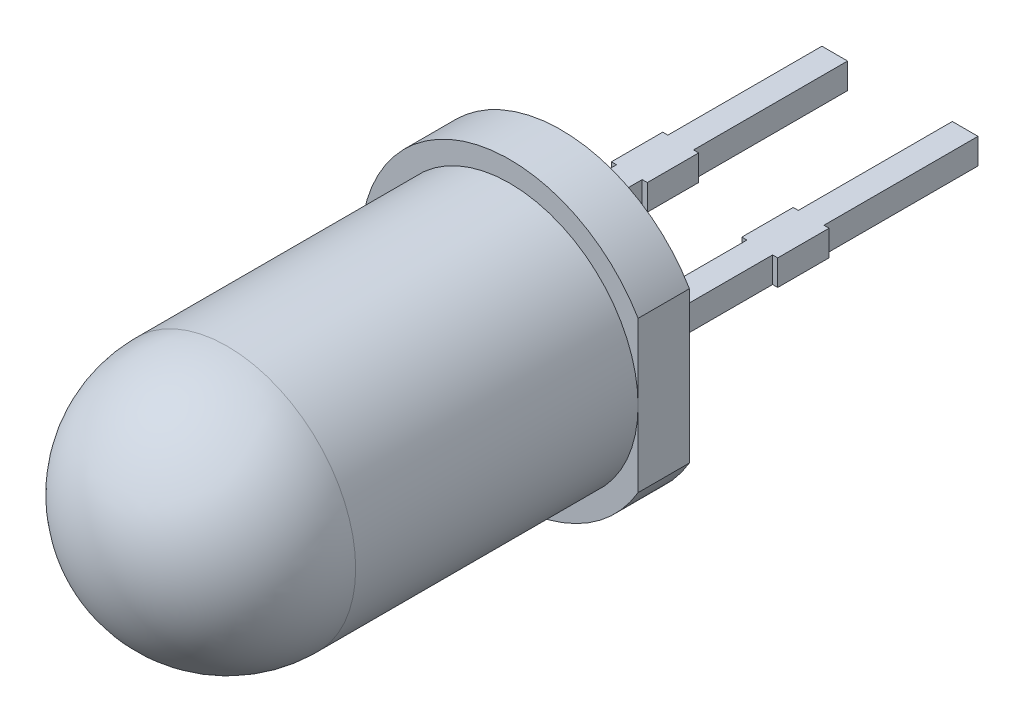
SolidWorks part; units mm, degrees
ref_plane "Front" through (0, 0, 0) normal (0, 0, 1) x (1, 0, 0)
ref_plane "Top" through (0, 0, 0) normal (0, 1, 0) x (1, 0, 0)
ref_plane "Right" through (0, 0, 0) normal (1, 0, 0) x (0, 0, -1)
sketch "Эскиз1" plane through (0, 0, 0) normal (0, -1, 0) x (1, 0, 0)
  line L0 (1.27, 0) -> (-1.27, 0) construction
  line L3 (-1.27, -3) -> (-1.27, 3.6) construction
  line L4 (-1.52, 3.6) -> (-1.52, 1)
  line L5 (-1.52, 1) -> (-1.62, 1)
  line L6 (-1.62, 1) -> (-1.62, 0)
  line L7 (-1.62, 0) -> (-1.52, 0)
  line L8 (-1.52, 0) -> (-1.52, -3)
  line L9 (-1.52, -3) -> (-1.02, -3)
  line L10 (-1.02, 1) -> (-1.02, 0) construction
  line L11 (-1.52, 1) -> (-1.52, 0) construction
  line L12 (-1.02, 0) -> (-1.02, -3)
  line L13 (-0.92, 0) -> (-1.02, 0)
  line L14 (-0.92, 1) -> (-0.92, 0)
  line L15 (-1.02, 1) -> (-0.92, 1)
  line L16 (-1.02, 3.6) -> (-1.02, 1)
  line L17 (1.52, 1) -> (1.52, 0) construction
  line L18 (1.02, 1) -> (1.02, 0) construction
  line L19 (1.02, 3.6) -> (1.02, 1)
  line L20 (1.02, 1) -> (0.92, 1)
  line L21 (0.92, 1) -> (0.92, 0)
  line L22 (0.92, 0) -> (1.02, 0)
  line L23 (1.02, 0) -> (1.02, -3)
  line L24 (1.52, -3) -> (1.02, -3)
  line L25 (1.52, 0) -> (1.52, -3)
  line L26 (1.62, 0) -> (1.52, 0)
  line L27 (1.62, 1) -> (1.62, 0)
  line L28 (1.52, 1) -> (1.62, 1)
  line L29 (1.52, 3.6) -> (1.52, 1)
  line L30 (1.27, -3) -> (1.27, 3.6) construction
  line L59 (-1.52, 3.6) -> (-1.02, 3.6)
  line L60 (1.02, 3.6) -> (1.52, 3.6)
  line L61 (-1.02, 3.6) -> (1.02, 3.6) construction
  point P19 (-1.27, -3)
  point P34 (1.27, -3)
  dimension "D4" = 2.6
  dimension "D1" = 0.5
  dimension "D2" = 2.54
  dimension "D3" = 0.7
  dimension "D5" = 1
  dimension "D6" = 3
extrude "Бобышка-Вытянуть1" add sketch "Эскиз1" along normal mid plane 0.5
sketch "Эскиз2" plane through (0, 0, 0) normal (0, 1, 0) x (1, 0, 0)
  line L0 (0, -3.6) -> (0, -12.6)
  line L1 (2.5, -10.1) -> (2.5, -4.6)
  line L2 (2.9, -3.6) -> (0, -3.6)
  line L3 (2.5, -4.6) -> (2.9, -4.6)
  line L4 (2.9, -4.6) -> (2.9, -3.6)
  line L5 (1.52, -3.6) -> (1.02, -3.6) construction
  line L6 (0, -3.6) -> (0, 0) construction
  arc A0 (2.5, -10.1) -> (0, -12.6) centre (0, -10.1) cw
  dimension "D1" = 5
  dimension "D2" = 5.8
  dimension "D3" = 1
  dimension "D4" = 9
revolve "Повернуть1" add sketch "Эскиз2" angle 360 about L6
sketch "Эскиз3" plane through (0, 0, 4.6) normal (0, 0, 1) x (1, 0, 0)
  line L0 (2.5, 1.4697) -> (2.5, -1.4697)
  circle A0 centre (0, 0) radius 2.5 construction
  circle A1 centre (0, 0) radius 2.9 construction
  arc A3 (2.5, 1.4697) -> (2.5, -1.4697) centre (0, 0) cw
extrude "Вырез-Вытянуть1" cut sketch "Эскиз3" against normal up to next
